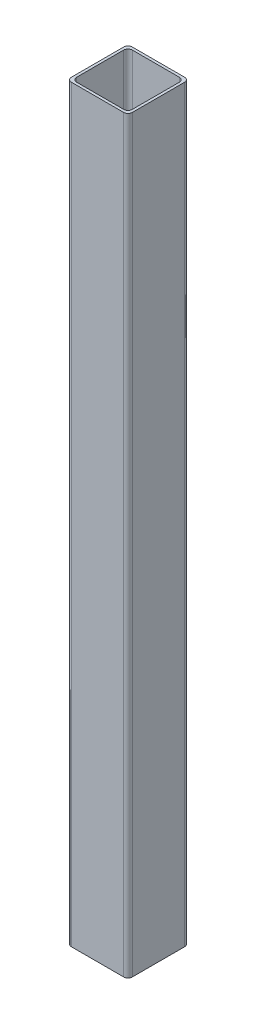
SolidWorks part; units mm, degrees
ref_plane "Front Plane" through (0, 0, 0) normal (0, 0, 1) x (1, 0, 0)
ref_plane "Top Plane" through (0, 0, 0) normal (0, 1, 0) x (1, 0, 0)
ref_plane "Right Plane" through (0, 0, 0) normal (1, 0, 0) x (0, 0, -1)
sketch "Sketch1" plane through (0, 0, 0) normal (0, 1, 0) x (1, 0, 0)
  line L0 (3, 67) -> (67, 67)
  line L1 (0, 0) -> (70, 0)
  line L2 (0, 0) -> (0, 70)
  line L3 (0, 70) -> (70, 70)
  line L4 (70, 0) -> (70, 70)
  line L5 (67, 3) -> (67, 67)
  line L6 (3, 3) -> (67, 3)
  line L7 (3, 3) -> (3, 67)
  dimension "D1" = 70
  dimension "D2" = 70
  dimension "D3" = 3
extrude "Boss-Extrude1" add sketch "Sketch1" along normal blind 860 contours L7 L6 L5 L0 | L1 L4 L3 L2 L6 L7 L0 L5
fillet "Fillet1" radius 5 8 edges at (70, 430, 0) (67, 430, -3) (70, 430, -70) (67, 430, -67) (3, 430, -67) (0, 430, -70) (0, 430, 0) (3, 430, -3)
